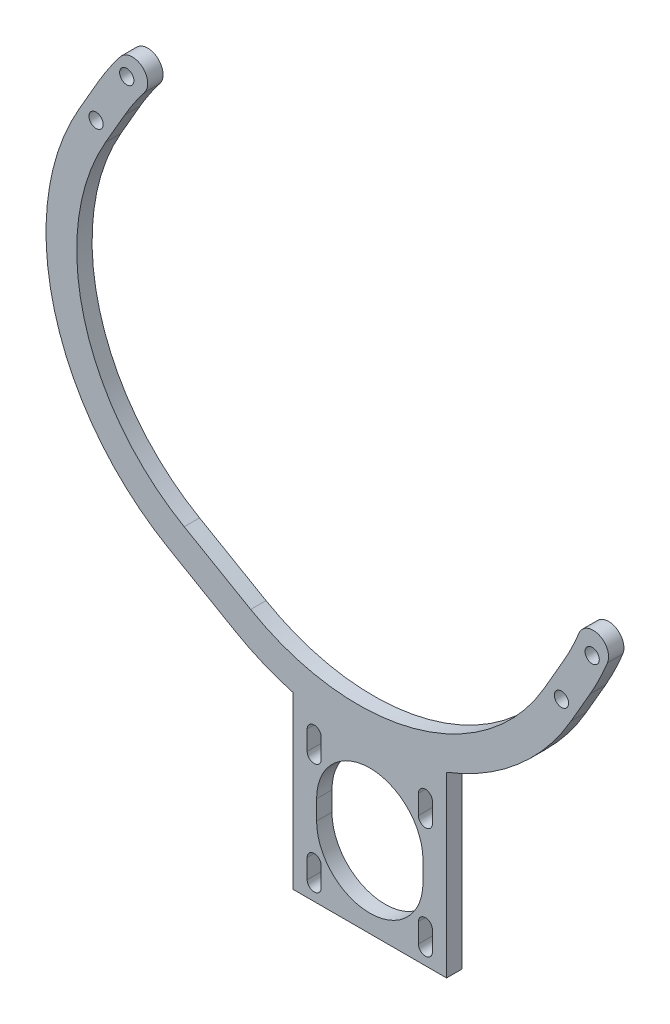
SolidWorks part; units mm, degrees
ref_plane "Front Plane" through (0, 0, 0) normal (0, 0, 1) x (1, 0, 0)
ref_plane "Top Plane" through (0, 0, 0) normal (0, 1, 0) x (1, 0, 0)
ref_plane "Right Plane" through (0, 0, 0) normal (1, 0, 0) x (0, 0, -1)
sketch "Sketch1" plane through (0, 0, -14.157) normal (0, 0, -1) x (-1, 0, 0)
  line L0 (-49.1723, -34.5021) -> (-53.1411, -27.628)
  line L1 (-2.2729, 1.7407) -> (29.3872, -53.0962) construction
  line L2 (20.2218, -53.0962) -> (27.0959, -49.1274)
  line L3 (33.9699, -45.1587) -> (20.2218, -53.0962) construction
  line L4 (17.0468, -47.5969) -> (23.9209, -43.6282)
  line L5 (-43.6731, -31.3271) -> (-47.6418, -24.453)
  line L6 (47.0648, 21.0604) -> (43.096, 27.9345)
  line L7 (30.7949, -39.6594) -> (23.9209, -43.6282)
  line L8 (33.9699, -45.1587) -> (27.0959, -49.1274)
  line L9 (52.564, 24.2354) -> (48.5953, 31.1095)
  arc A0 (-53.1411, -27.628) -> (-56.7299, -20.2712) centre (-2.2729, 1.7407) cw
  arc A3 (-61.0104, 1.7407) -> (-53.1411, -27.628) centre (-2.2729, 1.7407) ccw construction
  circle A4 centre (-53.5664, -20.5413) radius 1.1303 construction
  arc A5 (-49.1723, -34.5021) -> (20.2218, -53.0962) centre (-5.1782, -9.1021) ccw
  arc A6 (-43.6731, -31.3271) -> (17.0468, -47.5969) centre (-5.1782, -9.1021) ccw
  arc A7 (-47.6418, -24.453) -> (-50.8427, -17.8916) centre (-2.2729, 1.7407) cw
  arc A8 (-56.7299, -20.2712) -> (-50.8427, -17.8916) centre (-53.7863, -19.0814) cw
  arc A9 (44.0185, 37.8959) -> (39.014, 33.9872) centre (41.5163, 35.9416) ccw
  arc A10 (43.096, 27.9345) -> (39.014, 33.9872) centre (-2.2729, 1.7407) ccw
  arc A11 (47.0648, 21.0604) -> (30.7949, -39.6594) centre (8.5699, -1.1646) cw
  arc A12 (52.564, 24.2354) -> (33.9699, -45.1587) centre (8.5699, -1.1646) cw
  arc A13 (48.5953, 31.1095) -> (44.0185, 37.8959) centre (-2.2729, 1.7407) ccw
  dimension "D1" = 3.175
  dimension "D2" = 6.35
extrude "Boss-Extrude1" add sketch "Sketch1" along normal blind 3.175
ref_plane "Plane1" through (0, -58.42, 0) normal (0, 1, 0) x (-1, 0, 0)
sketch "Sketch2" plane through (8.6824, -58.42, 0) normal (0, 1, 0) x (-1, 0, 0)
  line L0 (1.098, -19.0836) -> (1.098, -10.0451) construction
  line L1 (28.9042, -15.7445) -> (42.6524, -15.7445) construction
  line L2 (28.9042, -17.332) -> (28.9042, -14.157) construction
  line L3 (42.6524, -17.332) -> (42.6524, -14.157) construction
  line L5 (16.973, -14.157) -> (-14.777, -14.157)
  line L6 (16.973, -14.157) -> (16.973, -17.332)
  line L7 (16.973, -17.332) -> (-14.777, -17.332)
  line L8 (-14.777, -14.157) -> (-14.777, -17.332)
  line L9 (16.973, -14.157) -> (-14.777, -17.332) construction
  line L10 (16.973, -17.332) -> (-14.777, -14.157) construction
  point P8 (1.098, -15.7445)
  dimension "D1" = 31.75
extrude "Boss-Extrude2" add sketch "Sketch2" against normal blind 34.925 and the other way blind 3.175
sketch "Sketch3" plane through (0, 0, -17.332) normal (0, 0, -1) x (-1, 0, 0)
  line L0 (8.2906, -93.345) -> (-23.4594, -93.345) construction
  line L18 (-19.0844, -67.17) -> (-19.0844, -63.17) construction
  line L19 (-20.5344, -67.17) -> (-20.5344, -63.17)
  line L20 (-17.6344, -67.17) -> (-17.6344, -63.17)
  line L21 (3.9156, -67.17) -> (3.9156, -63.17) construction
  line L22 (2.4656, -67.17) -> (2.4656, -63.17)
  line L23 (5.3656, -67.17) -> (5.3656, -63.17)
  line L24 (-19.0844, -90.17) -> (-19.0844, -86.17) construction
  line L25 (-20.5344, -90.17) -> (-20.5344, -86.17)
  line L26 (-17.6344, -90.17) -> (-17.6344, -86.17)
  line L27 (3.9156, -90.17) -> (3.9156, -86.17) construction
  line L28 (2.4656, -90.17) -> (2.4656, -86.17)
  line L29 (5.3656, -90.17) -> (5.3656, -86.17)
  line L30 (-19.0844, -67.17) -> (3.9156, -67.17) construction
  line L31 (-19.0844, -67.17) -> (-19.0844, -90.17) construction
  line L32 (-7.5844, -78.67) -> (-7.5844, -74.67) construction
  line L33 (-18.5844, -78.67) -> (-18.5844, -74.67)
  line L34 (3.4156, -78.67) -> (3.4156, -74.67)
  arc A10 (-20.5344, -67.17) -> (-17.6344, -67.17) centre (-19.0844, -67.17) ccw
  arc A11 (-17.6344, -63.17) -> (-20.5344, -63.17) centre (-19.0844, -63.17) ccw
  arc A12 (2.4656, -67.17) -> (5.3656, -67.17) centre (3.9156, -67.17) ccw
  arc A13 (5.3656, -63.17) -> (2.4656, -63.17) centre (3.9156, -63.17) ccw
  arc A14 (-20.5344, -90.17) -> (-17.6344, -90.17) centre (-19.0844, -90.17) ccw
  arc A15 (-17.6344, -86.17) -> (-20.5344, -86.17) centre (-19.0844, -86.17) ccw
  arc A16 (2.4656, -90.17) -> (5.3656, -90.17) centre (3.9156, -90.17) ccw
  arc A17 (5.3656, -86.17) -> (2.4656, -86.17) centre (3.9156, -86.17) ccw
  arc A18 (-18.5844, -78.67) -> (3.4156, -78.67) centre (-7.5844, -78.67) ccw
  arc A19 (3.4156, -74.67) -> (-18.5844, -74.67) centre (-7.5844, -74.67) ccw
  point P2 (-7.5844, -93.345)
  point P40 (-19.0844, -65.17)
  point P47 (-7.5844, -76.67)
  point P50 (3.9156, -65.17)
  point P57 (-19.0844, -88.17)
  point P64 (3.9156, -88.17)
  dimension "D5" = 3.175
  dimension "D7" = 1.45
  dimension "D11" = 11
  dimension "D2" = 11.5
  dimension "D3" = 23
  dimension "D4" = 23
  dimension "D8" = 4
  dimension "D12" = 11.5
extrude "Cut-Extrude1" cut sketch "Sketch3" against normal through all
hole_wizard "#4 Clearance Hole1" positions "Sketch5" profile "Sketch4" hole size "#4" standard "Ansi Inch" end condition through all
sketch "Sketch5" plane through (0, 0, -17.332) normal (0, 0, -1) x (-1, 0, 0)
  circle A1 centre (-53.5664, -20.5413) radius 1.1303 construction
  circle A2 centre (49.0206, 24.0227) radius 1.1303 construction
  point P0 (-53.5664, -20.5413)
  point P5 (-47.2164, -31.5398)
  point P8 (42.6706, 35.0212)
  point P11 (49.0206, 24.0227)
sketch "Sketch4" plane through (53.5664, -20.5413, -17.332) normal (1, 0, 0) x (0, 1, 0)
  line L0 (0, 0) -> (0, 3.175)
  line L1 (0, 3.175) -> (1.4732, 3.175)
  line L2 (1.4732, 3.175) -> (1.4732, 0)
  line L5 (1.4732, 0) -> (0, 0)
  line L11 (0, -6.35) -> (0, 107.95) construction
  dimension "Thru Hole Dia." = 2.9464
  dimension "Thru Hole Depth" = 3.175
